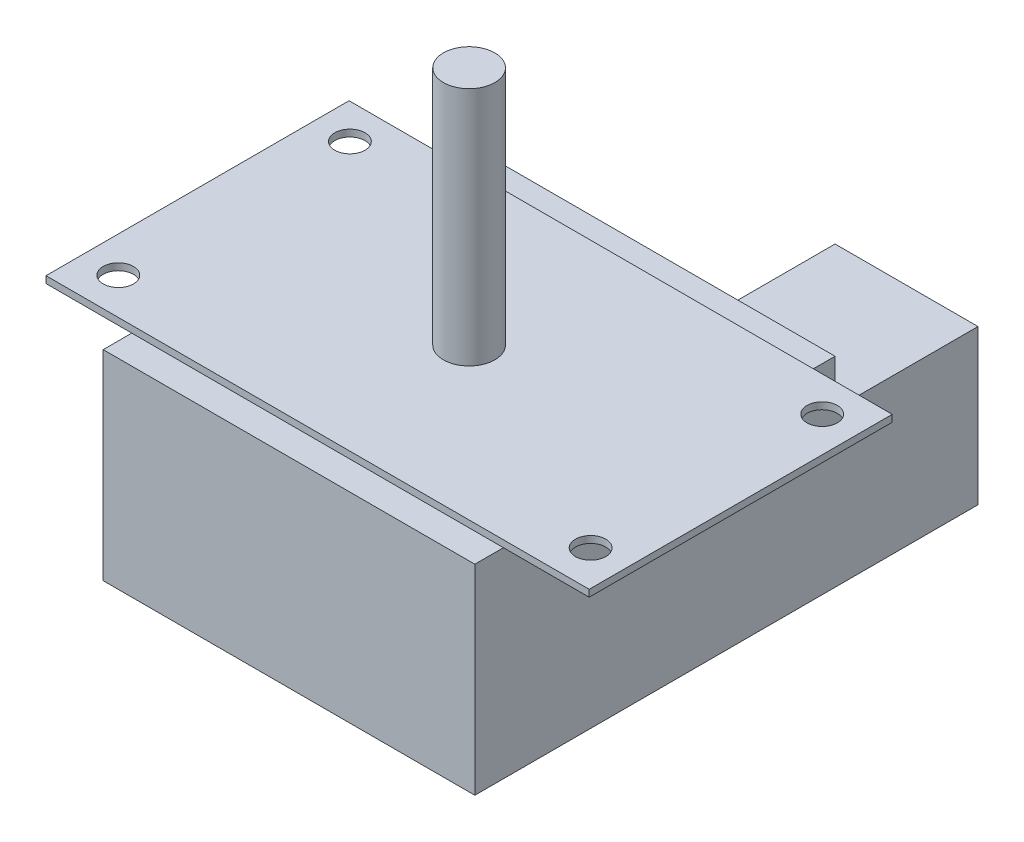
SolidWorks part; units mm, degrees
ref_plane "前视基准面" through (0, 0, 0) normal (0, 0, 1) x (1, 0, 0)
ref_plane "上视基准面" through (0, 0, 0) normal (0, 1, 0) x (1, 0, 0)
ref_plane "右视基准面" through (0, 0, 0) normal (1, 0, 0) x (0, 0, -1)
sketch "草图1" plane through (0, 0, 0) normal (0, 1, 0) x (1, 0, 0)
  line L1 (-47.5, -26.5) -> (47.5, -26.5)
  line L2 (-47.5, -26.5) -> (-47.5, 26.5)
  line L3 (-47.5, 26.5) -> (47.5, 26.5)
  line L4 (47.5, -26.5) -> (47.5, 26.5)
  line L5 (-47.5, -26.5) -> (47.5, 26.5) construction
  line L6 (-47.5, 26.5) -> (47.5, -26.5) construction
  text T0 "右上"
  point P0 (0, 0)
  dimension "D1" = 53
  dimension "D2" = 95
extrude "盖板" add sketch "草图1" along normal blind 1.2 contours L2 L1 L4 L3
sketch "草图6" plane through (0, 0, 0) normal (0, -1, 0) x (1, 0, 0)
  line L0 (47.5, -26.5) -> (32.5, -26.5) construction
  line L1 (-47.5, -26.5) -> (47.5, -26.5) construction
  line L2 (32.5, -26.5) -> (32.5, -56.5) construction
  line L3 (32.5, -56.5) -> (7.5, -56.5) construction
  line L4 (7.5, -26.5) -> (7.5, -31.5) construction
  line L5 (-47.5, -31.5) -> (-32.5, -31.5) construction
  line L6 (-32.5, 26.5) -> (-32.5, 31.5) construction
  line L7 (-47.5, 26.5) -> (47.5, 26.5) construction
  line L8 (32.5, -26.5) -> (32.5, 31.5) construction
  line L9 (32.5, 31.5) -> (-32.5, 31.5) construction
  line L10 (32.5, -56.5) -> (7.5, -56.5)
  line L27 (7.5, -56.5) -> (7.5, -31.5)
  line L28 (7.5, -31.5) -> (-32.5, -31.5)
  line L29 (-32.5, -31.5) -> (-32.5, 31.5)
  line L30 (-32.5, 31.5) -> (32.5, 31.5)
  line L31 (32.5, 31.5) -> (32.5, -56.5)
  dimension "D1" = 15
  dimension "D2" = 30
  dimension "D3" = 25
  dimension "D4" = 5
  dimension "D5" = 15
  dimension "D6" = 5
extrude "结构" add sketch "草图6" along normal blind 35
sketch "草图10" plane through (0, 0, 0) normal (0, 1, 0) x (1, 0, 0)
  line L1 (7.5, 31.5) -> (32.5, 31.5)
  line L2 (7.5, 31.5) -> (7.5, 56.5)
  line L3 (7.5, 56.5) -> (32.5, 56.5)
  line L4 (32.5, 31.5) -> (32.5, 56.5)
extrude "切除-拉伸1" cut sketch "草图10" against normal blind 8
sketch "草图7" plane through (0, 1.2, 0) normal (0, 1, 0) x (1, 0, 0)
  circle A0 centre (0, 0) radius 4.5
extrude "摇杆" add sketch "草图7" along normal blind 42
sketch "螺丝孔定位" plane through (0, 1.2, 0) normal (0, 1, 0) x (1, 0, 0)
  line L0 (47.5, 26.5) -> (47.5, 20.4) construction
  line L1 (47.5, -26.5) -> (47.5, 26.5) construction
  line L2 (47.5, 20.4) -> (41.35, 20.4) construction
  line L3 (-47.5, 26.5) -> (-47.5, 20.4) construction
  line L4 (-47.5, -26.5) -> (-47.5, 26.5) construction
  line L5 (-47.5, 20.4) -> (-41.25, 20.4) construction
  line L6 (47.5, -26.5) -> (47.5, -20.1) construction
  line L7 (47.5, -20.1) -> (41.35, -20.1) construction
  line L8 (-47.5, -26.5) -> (-47.5, -20.1) construction
  line L9 (-47.5, -20.1) -> (-41.25, -20.1) construction
  dimension "D1" = 6.1
  dimension "D2" = 6.15
  dimension "D3" = 6.1
  dimension "D4" = 6.25
  dimension "D5" = 6.4
  dimension "D6" = 6.15
  dimension "D7" = 6.4
  dimension "D8" = 6.25
hole_wizard "M5 间隙孔1" positions "草图8" profile "草图9" hole size "M5" standard "ISO" end condition up to next
sketch "草图8" plane through (0, 1.2, 0) normal (0, 1, 0) x (1, 0, 0)
  point P0 (-41.25, 20.4)
  point P2 (-41.25, -20.1)
  point P4 (41.35, -20.1)
  point P6 (41.35, 20.4)
sketch "草图9" plane through (-41.25, 1.2, -20.4) normal (1, 0, 0) x (0, 0, 1)
  line L0 (0, 0) -> (0, 1.2)
  line L1 (0, 1.2) -> (2.65, 1.2)
  line L2 (2.65, 1.2) -> (2.65, 0)
  line L5 (2.65, 0) -> (0, 0)
  line L11 (0, -6.35) -> (0, 107.95) construction
  dimension "通孔孔直径" = 5.3
  dimension "通孔孔深度" = 1.2
